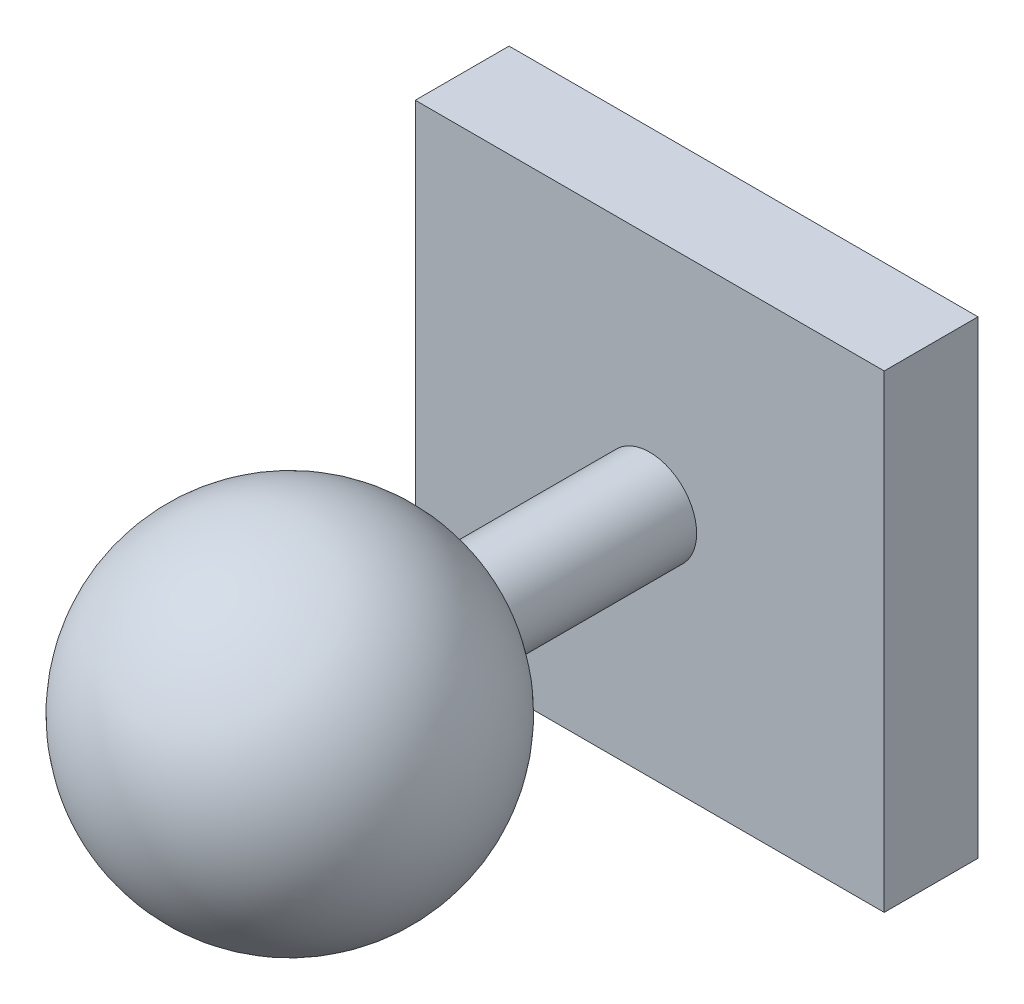
SolidWorks part; units mm, degrees
ref_plane "前视基准面" through (0, 0, 0) normal (0, 0, 1) x (1, 0, 0)
ref_plane "上视基准面" through (0, 0, 0) normal (0, 1, 0) x (1, 0, 0)
ref_plane "右视基准面" through (0, 0, 0) normal (1, 0, 0) x (0, 0, -1)
sketch "草图1" plane through (0, 0, 0) normal (0, 0, 1) x (1, 0, 0)
  line L1 (25, -25) -> (-25, -25)
  line L2 (25, -25) -> (25, 25)
  line L3 (25, 25) -> (-25, 25)
  line L4 (-25, -25) -> (-25, 25)
  line L5 (25, -25) -> (-25, 25) construction
  line L6 (25, 25) -> (-25, -25) construction
  point P0 (0, 0)
  dimension "D1" = 50
  dimension "D2" = 50
extrude "凸台-拉伸1" add sketch "草图1" along normal blind 10
sketch "草图2" plane through (0, 0, 10) normal (0, 0, 1) x (1, 0, 0)
  circle A0 centre (0, 0) radius 5
extrude "凸台-拉伸2" add sketch "草图2" along normal blind 20
sketch "草图4" plane through (0, 0, 0) normal (0, 1, 0) x (1, 0, 0)
  line L0 (0, -30) -> (0, -66.7661)
  arc A0 (0, -30) -> (0, -66.7661) centre (0, -48.3831) ccw
revolve "旋转16" add sketch "草图4" angle 360 mid plane about L0
sketch "草图5" plane through (0, 0, 0) normal (0, 0, -1) x (-1, 0, 0)
  circle A0 centre (0, 0) radius 5
extrude "切除-拉伸3" cut sketch "草图5" against normal blind 5
